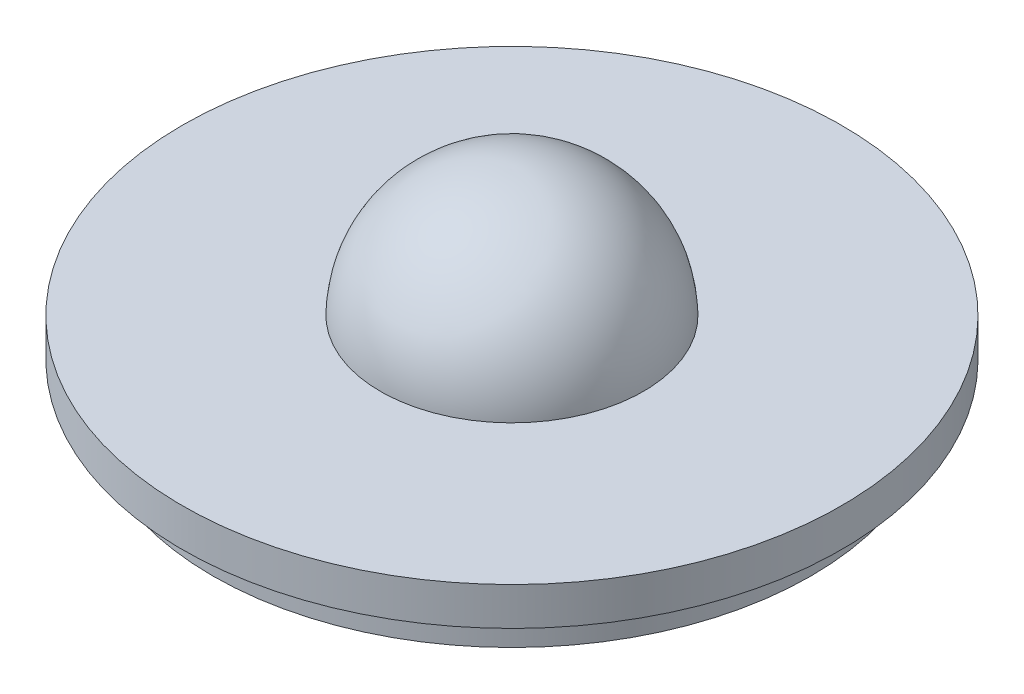
SolidWorks part; units mm, degrees
ref_plane "Alzado" through (0, 0, 0) normal (0, 0, 1) x (1, 0, 0)
ref_plane "Planta" through (0, 0, 0) normal (0, 1, 0) x (1, 0, 0)
ref_plane "Vista lateral" through (0, 0, 0) normal (1, 0, 0) x (0, 0, -1)
sketch "Croquis1" plane through (0, 0, 0) normal (0, 0, 1) x (1, 0, 0)
  line L0 (-4.9916, 5.9754) -> (-4.9916, -4.0246) construction
  line L1 (-27.6916, -4.7774) -> (-27.6916, -1.7774)
  line L2 (-27.6916, -4.7774) -> (-28.5916, -4.7774)
  line L3 (-28.5916, -4.7774) -> (-28.5916, -1.7774)
  line L4 (-28.5916, -1.7774) -> (-30.9916, -1.7774)
  line L5 (-30.9916, -1.7774) -> (-30.9916, 1.2226)
  line L6 (-30.9916, 1.2226) -> (-15.3707, 1.2226)
  line L7 (-4.9916, 1.2226) -> (-4.9916, 11.2226) construction
  line L8 (-27.6916, -1.7774) -> (-4.9916, -1.7774)
  line L9 (-4.9916, -1.7774) -> (-4.9916, 11.2226)
  arc A0 (-15.3707, 1.2226) -> (-4.9916, 11.2226) centre (-5.1812, 1.033) cw
  point P6 (-28.5916, -3.2774)
  dimension "D10" = 10.1913
  dimension "D1" = 10
  dimension "D2" = 0.9
  dimension "D3" = 23.6
  dimension "D4" = 3
  dimension "D5" = 3
  dimension "D6" = 3
  dimension "D7" = 2.4
  dimension "D8" = 10
  dimension "D9" = 10.379
revolve "Revolución1" add sketch "Croquis1" angle 360 about L0
